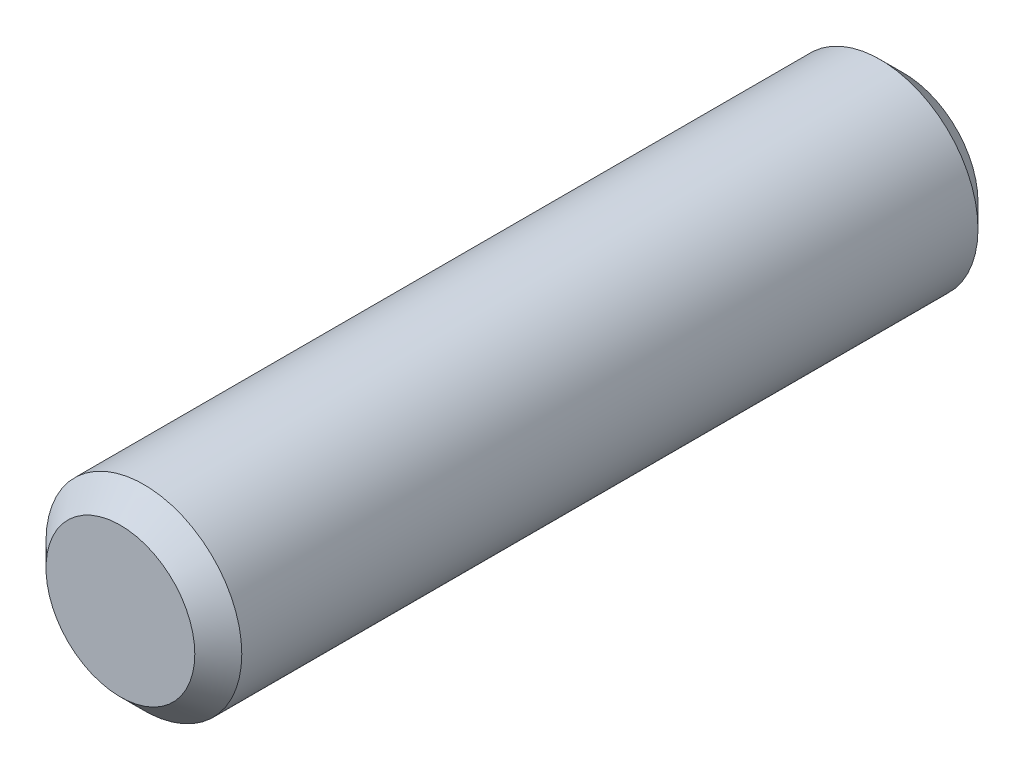
SolidWorks part; units mm, degrees
ref_plane "Front Plane" through (0, 0, 0) normal (0, 0, 1) x (1, 0, 0)
ref_plane "Top Plane" through (0, 0, 0) normal (0, 1, 0) x (1, 0, 0)
ref_plane "Right Plane" through (0, 0, 0) normal (1, 0, 0) x (0, 0, -1)
sketch "Sketch1" plane through (0, 0, 0) normal (0, 0, 1) x (1, 0, 0)
  circle A0 centre (0, 0) radius 3.175
  dimension "D1" = 6.35
extrude "Boss-Extrude1" add sketch "Sketch1" along normal blind 25.4
chamfer "Chamfer1" distance 0.762 2 edges at (3.175, 0, 0) (3.175, 0, 25.4)
